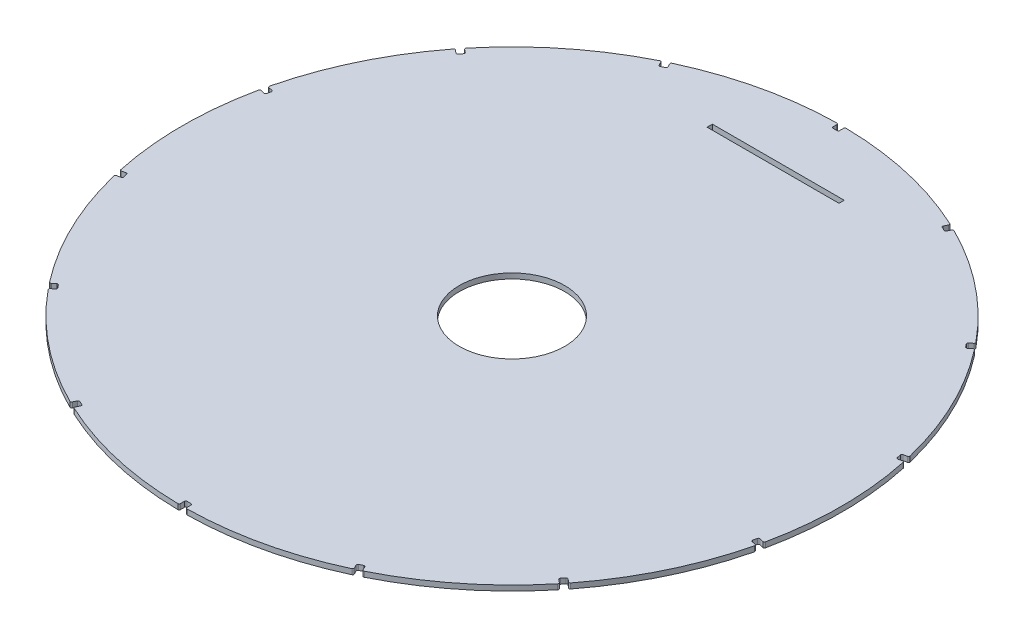
SolidWorks part; units mm, degrees
ref_plane "Front Plane" through (0, 0, 0) normal (0, 0, 1) x (1, 0, 0)
ref_plane "Top Plane" through (0, 0, 0) normal (0, 1, 0) x (1, 0, 0)
ref_plane "Right Plane" through (0, 0, 0) normal (1, 0, 0) x (0, 0, -1)
sketch "Sketch1" plane through (0, 0, 0) normal (0, 1, 0) x (1, 0, 0)
  circle A0 centre (0, 0) radius 250
extrude "Boss-Extrude1" add sketch "Sketch1" along normal blind 4
sketch "Sketch11" plane through (0, 4, 0) normal (0, 1, 0) x (1, 0, 0)
  line L1 (1.5, 245) -> (-1.5, 245)
  line L2 (2.5, 246) -> (2.5, 255)
  line L3 (2.5, 255) -> (-2.5, 255)
  line L4 (-2.5, 246) -> (-2.5, 255)
  line L5 (2.5, 245) -> (-2.5, 255) construction
  line L6 (2.5, 255) -> (-2.5, 245) construction
  circle A0 centre (0, 0) radius 250 construction
  arc A1 (2.5, 246) -> (1.5, 245) centre (1.5, 246) cw
  arc A2 (-1.5, 245) -> (-2.5, 246) centre (-1.5, 246) cw
  point P0 (0, 250)
  dimension "D3" = 1
  dimension "D1" = 10
  dimension "D2" = 5
extrude "Cut-Extrude5" cut sketch "Sketch11" against normal blind 4
fillet "Fillet1" radius 1 2 edges at (2.5, 2, -249.9875) (-2.5, 2, -249.9875)
pattern_circular "CirPattern1" count 14 over 360 about axis through (0, 0, 0) along (0, 1, 0) of "Cut-Extrude5", "Fillet1"
sketch "Sketch12" plane through (0, 4, 0) normal (0, 1, 0) x (1, 0, 0)
  circle A0 centre (0, 0) radius 40
extrude "Cut-Extrude6" cut sketch "Sketch12" against normal blind 10
sketch "Sketch13" plane through (0, 4, 0) normal (0, 1, 0) x (1, 0, 0)
  circle A0 centre (-162, -130) radius 2.1
  circle A1 centre (-162, -110) radius 2.1
  circle A2 centre (126, -146) radius 2.1
  circle A3 centre (146, -146) radius 2.1
  circle A4 centre (-146, -147) radius 2.1
  circle A5 centre (-126, -147) radius 2.1
  circle A6 centre (163, -130) radius 2.1
  circle A7 centre (163, -110) radius 2.1
  circle A8 centre (-163, 110) radius 2.1
  circle A9 centre (-163, 130) radius 2.1
  circle A10 centre (-146, 146) radius 2.1
  circle A11 centre (-126, 146) radius 2.1
  circle A12 centre (126, 147) radius 2.1
  circle A13 centre (146, 147) radius 2.1
  circle A14 centre (162, 110) radius 2.1
  circle A15 centre (162, 130) radius 2.1
sketch "Sketch16" plane through (0, 4, 0) normal (0, 1, 0) x (1, 0, 0)
  line L1 (50, 198) -> (-50, 198)
  line L2 (50, 198) -> (50, 202)
  line L3 (50, 202) -> (-50, 202)
  line L4 (-50, 198) -> (-50, 202)
  line L5 (50, 198) -> (-50, 202) construction
  line L6 (50, 202) -> (-50, 198) construction
  point P0 (0, 200)
  dimension "D1" = 4
  dimension "D2" = 100
  dimension "D3" = 0
  dimension "D4" = 200
extrude "Cut-Extrude10" cut sketch "Sketch16" against normal blind 100
